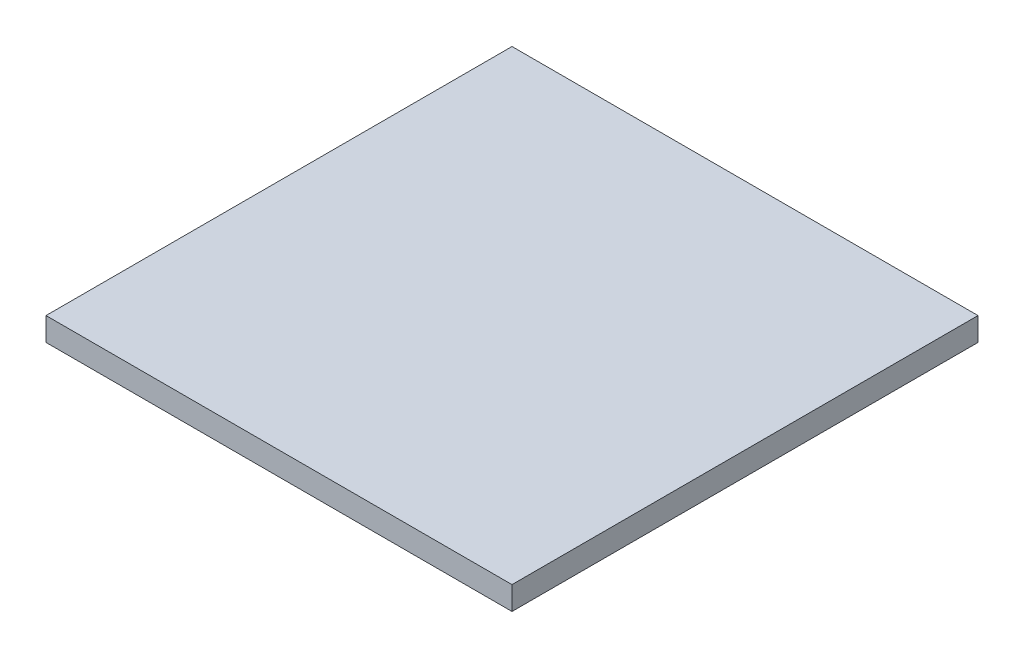
SolidWorks part; units mm, degrees
material "7075-T6, Plate (SS)"
ref_plane "Front Plane" through (0, 0, 0) normal (0, 0, 1) x (1, 0, 0)
ref_plane "Top Plane" through (0, 0, 0) normal (0, 1, 0) x (1, 0, 0)
ref_plane "Right Plane" through (0, 0, 0) normal (1, 0, 0) x (0, 0, -1)
sketch "Sketch1" plane through (0, 0, 0) normal (0, 1, 0) x (1, 0, 0)
  line L1 (-63.5, -63.5) -> (63.5, -63.5)
  line L2 (-63.5, -63.5) -> (-63.5, 63.5)
  line L3 (-63.5, 63.5) -> (63.5, 63.5)
  line L4 (63.5, -63.5) -> (63.5, 63.5)
  line L5 (-63.5, -63.5) -> (63.5, 63.5) construction
  line L6 (-63.5, 63.5) -> (63.5, -63.5) construction
  point P0 (0, 0)
  dimension "D1" = 127
  dimension "D2" = 127
extrude "Boss-Extrude1" add sketch "Sketch1" along normal blind 6.35
